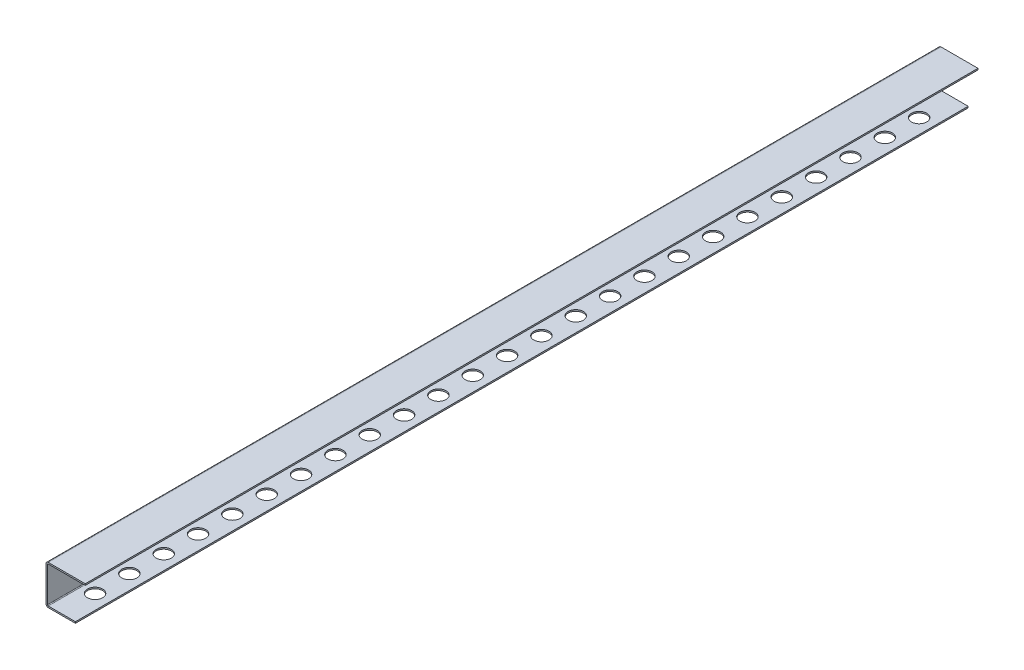
SolidWorks part; units mm, degrees
ref_plane "Front Plane" through (0, 0, 0) normal (0, 0, 1) x (1, 0, 0)
ref_plane "Top Plane" through (0, 0, 0) normal (0, 1, 0) x (1, 0, 0)
ref_plane "Right Plane" through (0, 0, 0) normal (1, 0, 0) x (0, 0, -1)
sketch "Sketch1" plane through (0, 0, 0) normal (0, 0, 1) x (1, 0, 0)
  line L0 (0, 0) -> (30, 0)
  line L1 (30, 0) -> (30, 1.5)
  line L2 (30, 1.5) -> (1.5, 1.5)
  line L3 (1.5, 1.5) -> (1.5, 38.5)
  line L4 (1.5, 38.5) -> (40, 38.5)
  line L5 (40, 38.5) -> (40, 40)
  line L6 (40, 40) -> (0, 40)
  line L7 (0, 40) -> (0, 0)
  dimension "D1" = 40
  dimension "D2" = 40
  dimension "D3" = 30
  dimension "D4" = 1.5
  dimension "D5" = 37
  dimension "D6" = 1.5
extrude "Boss-Extrude1" add sketch "Sketch1" against normal blind 900 and the other way blind 10
sketch "Sketch2" plane through (0, 0, 0) normal (0, -1, 0) x (1, 0, 0)
  line L0 (15, -900) -> (15, 10) construction
  line L1 (0, -900) -> (30, -900) construction
  line L2 (0, 10) -> (30, 10) construction
  circle A0 centre (15, -25) radius 7.75
  circle A1 centre (15, -60) radius 7.75
  circle A2 centre (15, -95) radius 7.75
  circle A3 centre (15, -130) radius 7.75
  circle A4 centre (15, -165) radius 7.75
  circle A5 centre (15, -200) radius 7.75
  circle A6 centre (15, -235) radius 7.75
  circle A7 centre (15, -270) radius 7.75
  circle A8 centre (15, -305) radius 7.75
  circle A9 centre (15, -340) radius 7.75
  circle A10 centre (15, -375) radius 7.75
  circle A11 centre (15, -410) radius 7.75
  circle A12 centre (15, -445) radius 7.75
  circle A13 centre (15, -480) radius 7.75
  circle A14 centre (15, -515) radius 7.75
  circle A15 centre (15, -550) radius 7.75
  circle A16 centre (15, -585) radius 7.75
  circle A17 centre (15, -620) radius 7.75
  circle A18 centre (15, -655) radius 7.75
  circle A19 centre (15, -690) radius 7.75
  circle A20 centre (15, -725) radius 7.75
  circle A21 centre (15, -760) radius 7.75
  circle A22 centre (15, -795) radius 7.75
  circle A23 centre (15, -830) radius 7.75
  circle A24 centre (15, -865) radius 7.75
  dimension "D1" = 15.5
  dimension "D2" = 35
  dimension "D3" = 25
extrude "Cut-Extrude2" cut sketch "Sketch2" against normal up to next (1.5 mm away)
fillet "Fillet1" radius 2.3 2 edges at (0, 0, -445) (0, 40, -445)
fillet "Fillet2" radius 0.8 2 edges at (1.5, 1.5, -445) (1.5, 38.5, -445)
